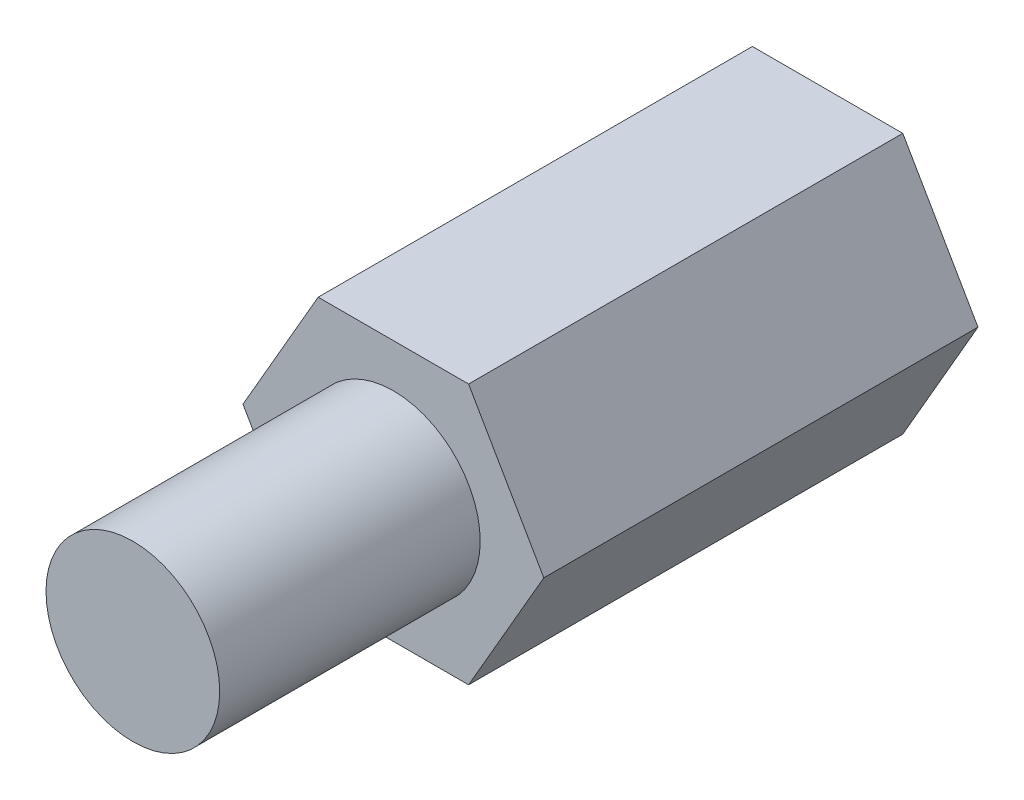
SolidWorks part; units mm, degrees
ref_plane "정면" through (0, 0, 0) normal (0, 0, 1) x (1, 0, 0)
ref_plane "윗면" through (0, 0, 0) normal (0, 1, 0) x (1, 0, 0)
ref_plane "우측면" through (0, 0, 0) normal (1, 0, 0) x (0, 0, -1)
sketch "스케치1" plane through (0, 0, 0) normal (0, 0, 1) x (1, 0, 0)
  line L1 (0.866, -1.5) -> (1.7321, 0)
  line L2 (1.7321, 0) -> (0.866, 1.5)
  line L3 (0.866, 1.5) -> (-0.866, 1.5)
  line L4 (-0.866, 1.5) -> (-1.7321, 0)
  line L5 (-1.7321, 0) -> (-0.866, -1.5)
  line L6 (-0.866, -1.5) -> (0.866, -1.5)
  circle A0 centre (0, 0) radius 1.5 construction
  dimension "D1" = 3
extrude "보스-돌출1" add sketch "스케치1" along normal blind 5
sketch "스케치2" plane through (0, 0, 5) normal (0, 0, 1) x (1, 0, 0)
  circle A0 centre (0, 0) radius 1
  dimension "D1" = 2
extrude "보스-돌출2" add sketch "스케치2" along normal blind 3
sketch "스케치3" plane through (0, 0, 0) normal (0, 0, -1) x (-1, 0, 0)
  point P0 (0, 0)
hole_wizard "M2 여유 구멍1" positions "스케치6" profile "스케치7" hole size "M2" standard "Ansi Metric"
sketch "스케치6" plane through (0, 0, 0) normal (0, 0, -1) x (-1, 0, 0)
  point P0 (0, 0)
sketch "스케치7" plane through (0, 0, 0) normal (1, 0, 0) x (0, 1, 0)
  line L0 (0, 0) -> (0, 3.721)
  line L1 (0, 3.721) -> (1.2, 3)
  line L2 (1.2, 3) -> (1.2, 0)
  line L5 (1.2, 0) -> (0, 0)
  line L10 (0, 3.721) -> (-1.2, 3) construction
  line L11 (0, -6.35) -> (0, 107.95) construction
  dimension "구멍 지름" = 2.4
  dimension "구멍 깊이" = 3
  dimension "드릴 각도" = 118
